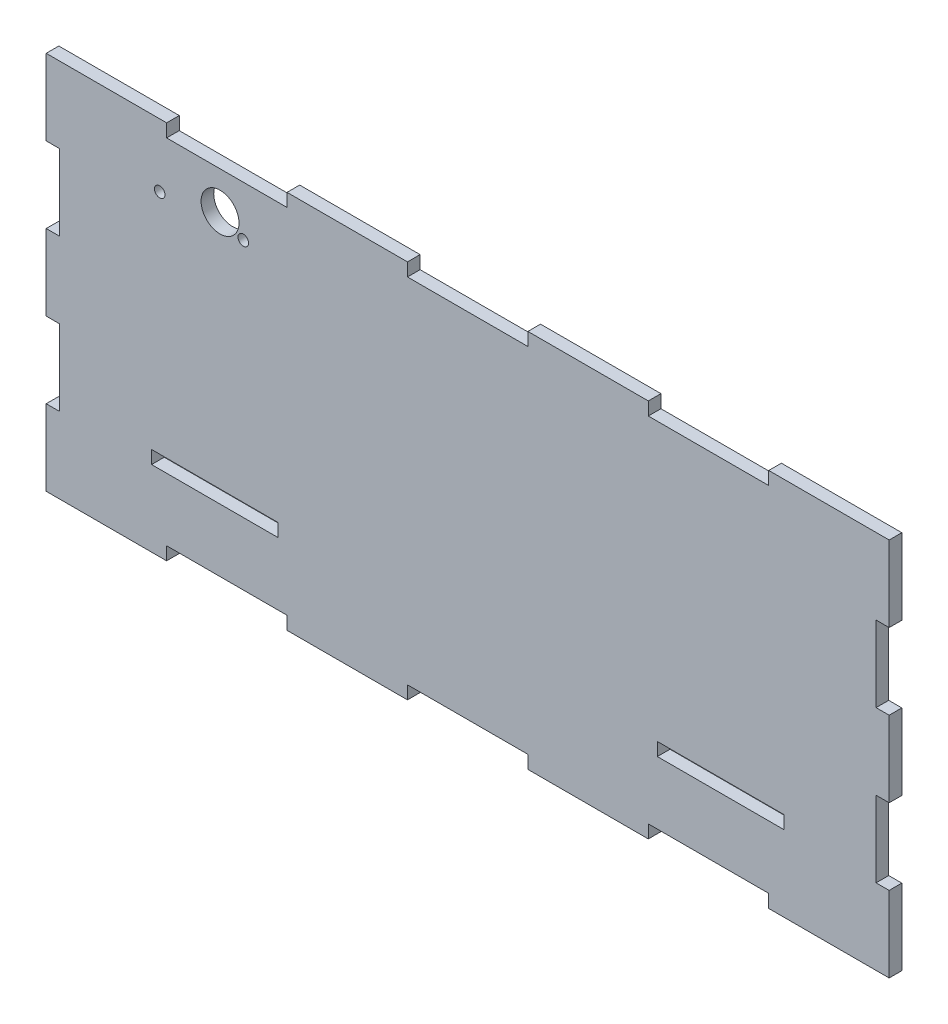
SolidWorks part; units mm, degrees
ref_plane "Alzado" through (0, 0, 0) normal (0, 0, 1) x (1, 0, 0)
ref_plane "Planta" through (0, 0, 0) normal (0, 1, 0) x (1, 0, 0)
ref_plane "Vista lateral" through (0, 0, 0) normal (1, 0, 0) x (0, 0, -1)
sketch "Croquis1" plane through (0, 0, 0) normal (0, 0, 1) x (1, 0, 0)
  line L0 (-100, 0) -> (100, 0) construction
  line L1 (-100, -45) -> (100, -45)
  line L2 (-100, -45) -> (-100, 45)
  line L3 (-100, 45) -> (100, 45)
  line L4 (100, -45) -> (100, 45)
  line L5 (-100, -45) -> (100, 45) construction
  line L6 (-100, 45) -> (100, -45) construction
  line L7 (-71.4286, 45) -> (-42.8571, 45)
  line L8 (-71.4286, 45) -> (-71.4286, 41.9)
  line L9 (-71.4286, 41.9) -> (-42.8571, 41.9)
  line L10 (-42.8571, 45) -> (-42.8571, 41.9)
  line L11 (-14.2857, 45) -> (14.2857, 45)
  line L12 (-14.2857, 45) -> (-14.2857, 41.9)
  line L13 (-14.2857, 41.9) -> (14.2857, 41.9)
  line L14 (14.2857, 45) -> (14.2857, 41.9)
  line L15 (42.8571, 45) -> (71.4286, 45)
  line L16 (42.8571, 45) -> (42.8571, 41.9)
  line L17 (42.8571, 41.9) -> (71.4286, 41.9)
  line L18 (71.4286, 45) -> (71.4286, 41.9)
  line L19 (-100, 27) -> (-96.9, 27)
  line L20 (-100, 27) -> (-100, 9)
  line L21 (-100, 9) -> (-96.9, 9)
  line L22 (-96.9, 27) -> (-96.9, 9)
  line L23 (-100, -9) -> (-96.9, -9)
  line L24 (-100, -9) -> (-100, -27)
  line L25 (-100, -27) -> (-96.9, -27)
  line L26 (-96.9, -9) -> (-96.9, -27)
  line L27 (0, 45) -> (0, -45) construction
  line L28 (100, -27) -> (96.9, -27)
  line L29 (96.9, -9) -> (96.9, -27)
  line L30 (100, -9) -> (96.9, -9)
  line L31 (100, -9) -> (100, -27)
  line L32 (100, 9) -> (96.9, 9)
  line L33 (96.9, 27) -> (96.9, 9)
  line L34 (100, 27) -> (96.9, 27)
  line L35 (100, 27) -> (100, 9)
  line L36 (71.4286, -45) -> (71.4286, -41.9)
  line L37 (42.8571, -41.9) -> (71.4286, -41.9)
  line L38 (42.8571, -45) -> (42.8571, -41.9)
  line L39 (14.2857, -45) -> (14.2857, -41.9)
  line L40 (-14.2857, -41.9) -> (14.2857, -41.9)
  line L41 (-14.2857, -45) -> (-14.2857, -41.9)
  line L42 (-42.8571, -45) -> (-42.8571, -41.9)
  line L43 (-71.4286, -41.9) -> (-42.8571, -41.9)
  line L44 (-71.4286, -45) -> (-71.4286, -41.9)
  point P0 (0, 0)
  point P26 (-98.45, 27)
  dimension "D1" = 200
  dimension "D2" = 90
  dimension "D3" = 28.5714
  dimension "D4" = 28.5714
  dimension "D5" = 28.5714
  dimension "D6" = 28.5714
  dimension "D7" = 28.5714
  dimension "D8" = 28.5714
  dimension "D9" = 28.5714
  dimension "D10" = 3.1
  dimension "D11" = 18
  dimension "D12" = 18
  dimension "D13" = 18
  dimension "D14" = 18
  dimension "D15" = 18
  dimension "D16" = 3.1
extrude "Saliente-Extruir1" add sketch "Croquis1" along normal mid plane 3 contours L34 L4 L3 L18 L17 L16 L14 L13 L12 L10 L9 L8 L2 L19 L22 L21 L23 L26 L25 L1 L28 L29 L30 L32 L33
sketch "Croquis2" plane through (0, 0, 1.5) normal (0, 0, 1) x (1, 0, 0)
  line L0 (-100, -45) -> (-71.4286, -45) construction
  line L1 (-75, -23.9) -> (-45, -23.9)
  line L2 (-75, -23.9) -> (-75, -27)
  line L3 (-75, -27) -> (-45, -27)
  line L4 (-45, -23.9) -> (-45, -27)
  line L5 (45, -23.9) -> (75, -23.9)
  line L6 (45, -23.9) -> (45, -27)
  line L7 (45, -27) -> (75, -27)
  line L8 (75, -23.9) -> (75, -27)
  line L9 (0, 41.9) -> (0, -45) construction
  line L10 (-14.2857, 41.9) -> (14.2857, 41.9) construction
  dimension "D1" = 30
  dimension "D2" = 3.1
  dimension "D3" = 18
  dimension "D4" = 45
  dimension "D5" = 30
extrude "Cortar-Extruir1" cut sketch "Croquis2" against normal blind 10
sketch "Croquis6" plane through (0, 0, -1.5) normal (0, 0, -1) x (-1, 0, 0)
  line L0 (100, 0) -> (-100, 0) construction
  line L1 (53.2533, 30) -> (73.0533, 30) construction
  line L2 (53.2533, 30) -> (53.2533, 28.1601) construction
  line L3 (54.2533, 33) -> (54.2533, 22.154) construction
  circle A0 centre (53.2533, 30) radius 1.25
  circle A1 centre (73.0533, 30) radius 1.25
  circle A2 centre (58.7533, 33) radius 4.5
  dimension "D1" = 19.8
  dimension "D5" = 2.5
  dimension "D6" = 9
  dimension "D2" = 30
  dimension "D3" = 30
  dimension "D4" = 53.2533
  dimension "D7" = 3
  dimension "D8" = 1
extrude "Cortar-Extruir2" cut sketch "Croquis6" against normal blind 3
